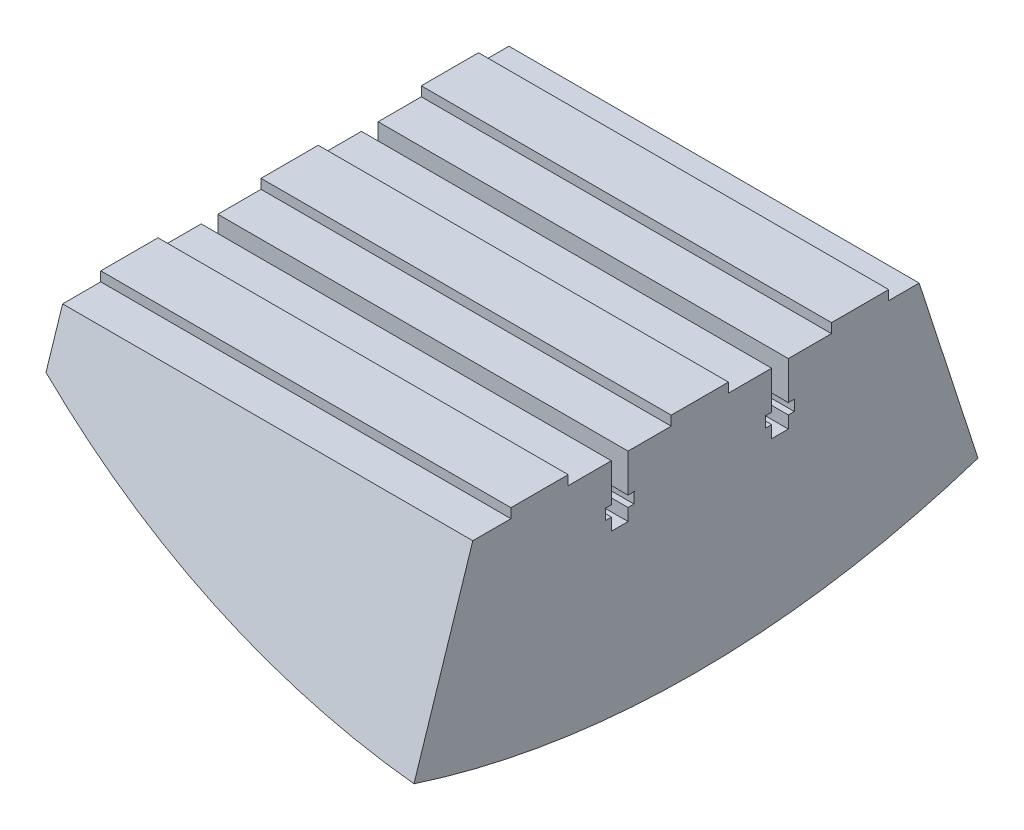
SolidWorks part; units mm, degrees
ref_plane "Front Plane" through (0, 0, 0) normal (0, 0, 1) x (1, 0, 0)
ref_plane "Top Plane" through (0, 0, 0) normal (0, 1, 0) x (1, 0, 0)
ref_plane "Right Plane" through (0, 0, 0) normal (1, 0, 0) x (0, 0, -1)
sketch "Sketch1" plane through (0, 0, 0) normal (0, 0, 1) x (1, 0, 0)
  line L0 (0, 0) -> (0, 125.3059) construction
  line L1 (0, 0) -> (-289.7399, 0) construction
  line L2 (-202.802, -227.5398) -> (-25.4, -227.5398)
  line L3 (-25.4, -227.5398) -> (-25.4, -303.7398)
  arc A0 (-25.4, -303.7398) -> (-202.802, -227.5398) centre (0, 0) cw
  dimension "D1" = 304.8
  dimension "D2" = 25.4
  dimension "D3" = 76.2
revolve "Revolve1" add sketch "Sketch1" angle 36 mid plane about L1
sketch "Sketch2" plane through (-25.4, 0, 0) normal (1, 0, 0) x (0, 0, -1)
  line L1 (-89.4432, -172.2284) -> (95.809, -172.2284)
  line L2 (-89.4432, -172.2284) -> (-89.4432, -228.6)
  line L3 (-89.4432, -228.6) -> (95.809, -228.6)
  line L4 (95.809, -172.2284) -> (95.809, -228.6)
  arc A0 (-70.3137, -216.4032) -> (70.3137, -216.4032) centre (0, 0) ccw construction
  dimension "D1" = 228.6
extrude "Cut-Extrude1" cut sketch "Sketch2" against normal through all
sketch "Sketch5" plane through (0, -228.6, 0) normal (0, 1, 0) x (1, 0, 0)
  line L0 (-187.4248, -74.2766) -> (-187.4248, 74.2766)
  line L1 (-187.4248, -74.2766) -> (-243.0799, -74.2766)
  line L2 (-187.4248, 74.2766) -> (-243.0799, 74.2766)
  line L3 (-243.0799, -74.2766) -> (-243.0799, 74.2766)
extrude "Cut-Extrude2" cut sketch "Sketch5" against normal through all
sketch "Sketch6" plane through (0, -228.6, 0) normal (0, 1, 0) x (1, 0, 0)
  line L0 (-187.4248, -74.2766) -> (-187.4248, 74.2766) construction
  line L1 (-25.4, -61.5766) -> (-187.4248, -61.5766)
  line L2 (-25.4, -61.5766) -> (-25.4, -42.5266)
  line L3 (-25.4, -42.5266) -> (-187.4248, -42.5266)
  line L4 (-187.4248, -61.5766) -> (-187.4248, -42.5266)
  line L5 (-25.4, -74.2766) -> (-187.4248, -74.2766) construction
  dimension "D1" = 19.05
  dimension "D2" = 12.7
extrude "Boss-Extrude1" add sketch "Sketch6" along normal blind 3.175
pattern_linear "LPattern1" count 3 spacing 53.34 along (0, 0, -1) of "Boss-Extrude1"
sketch "Sketch7" plane through (-25.4, 0, 0) normal (1, 0, 0) x (0, 0, -1)
  line L0 (-22.6035, -244.856) -> (-22.6035, -248.92)
  line L1 (-42.5266, -228.6) -> (-8.2366, -228.6) construction
  line L2 (-22.6035, -228.6) -> (-28.1598, -228.6)
  line L3 (-28.1598, -228.6) -> (-28.1598, -241.3)
  line L4 (-28.1598, -241.3) -> (-30.0171, -241.3)
  line L5 (-30.1441, -241.427) -> (-30.1441, -244.856)
  line L6 (-30.1441, -244.856) -> (-28.1598, -244.856)
  line L7 (-28.1598, -244.856) -> (-28.1598, -248.92)
  line L8 (-28.1598, -248.92) -> (-22.6035, -248.92)
  line L9 (-25.3816, -228.6) -> (-25.3816, -263.1045) construction
  line L10 (-20.6191, -244.856) -> (-22.6035, -244.856)
  line L11 (-20.6191, -241.427) -> (-20.6191, -244.856)
  line L12 (-22.6035, -241.3) -> (-20.7461, -241.3)
  line L13 (-22.6035, -228.6) -> (-22.6035, -241.3)
  arc A0 (-30.0171, -241.3) -> (-30.1441, -241.427) centre (-30.1441, -241.3) ccw
  arc A1 (-20.7461, -241.3) -> (-20.6191, -241.427) centre (-20.6191, -241.3) cw
  point P0 (-25.3816, -228.6)
  point P18 (-25.3816, -248.92)
  dimension "D4" = 2.7781
  dimension "D3" = 0.127
  dimension "D1" = 20.32
  dimension "D2" = 3.429
  dimension "D5" = 9.525
  dimension "D6" = 12.7
extrude "Cut-Extrude3" cut sketch "Sketch7" against normal through all
pattern_linear "LPattern2" count 2 spacing 53.34 along (0, 0, -1) of "Cut-Extrude3"
sketch "Sketch8" plane through (0, -225.425, 0) normal (0, 1, 0) x (1, 0, 0)
  line L0 (-25.4, -8.2366) -> (-25.4, 10.8134) construction
  line L1 (-215.6308, 85.3843) -> (-161.925, 85.3843)
  line L2 (-215.6308, 85.3843) -> (-215.6308, -110.6191)
  line L3 (-215.6308, -110.6191) -> (-161.925, -110.6191)
  line L4 (-161.925, 85.3843) -> (-161.925, -110.6191)
  dimension "D1" = 136.525
extrude "Cut-Extrude4" cut sketch "Sketch8" against normal through all
sketch "Sketch10" plane through (0, -225.425, 0) normal (0, 1, 0) x (1, 0, 0)
  line L0 (-25.4, 64.1534) -> (-25.4, -81.7503)
  line L1 (-38.862, 64.1534) -> (-38.862, -81.7503)
  line L2 (-52.324, 64.1534) -> (-52.324, -81.7503)
  line L3 (-65.786, 64.1534) -> (-65.786, -81.7503)
  line L4 (-79.248, 64.1534) -> (-79.248, -81.7503)
  line L5 (-92.71, 64.1534) -> (-92.71, -81.7503)
  line L6 (-106.172, 64.1534) -> (-106.172, -81.7503)
  line L7 (-119.634, 64.1534) -> (-119.634, -81.7503)
  line L8 (-133.096, 64.1534) -> (-133.096, -81.7503)
  line L9 (-146.558, 64.1534) -> (-146.558, -81.7503)
  line L10 (-160.02, 64.1534) -> (-160.02, -81.7503)
  dimension "D1" = 11
